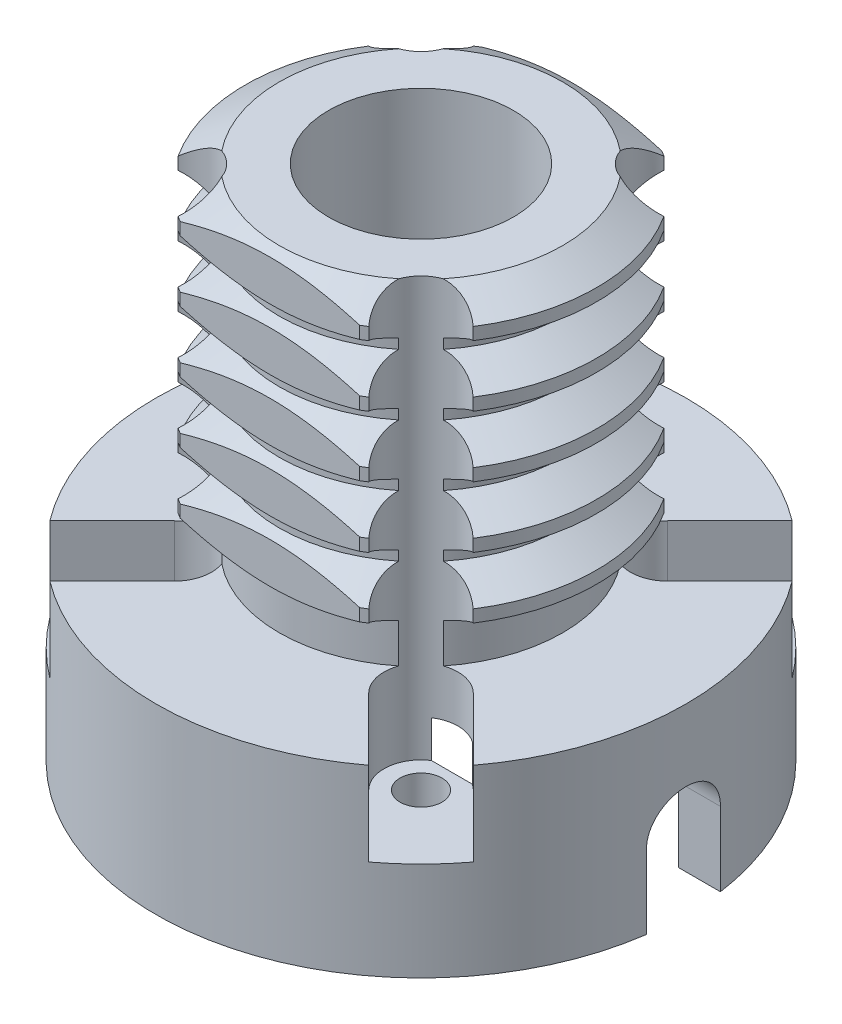
SolidWorks part; units mm, degrees
ref_plane "前视基准面" through (0, 0, 0) normal (0, 0, 1) x (1, 0, 0)
ref_plane "上视基准面" through (0, 0, 0) normal (0, 1, 0) x (1, 0, 0)
ref_plane "右视基准面" through (0, 0, 0) normal (1, 0, 0) x (0, 0, -1)
other "Configuration Table"
sketch "草图1" plane through (0, 0, 0) normal (0, 1, 0) x (1, 0, 0)
  circle A0 centre (0, 0) radius 21.5
  dimension "D1" = 43
extrude "凸台-拉伸1" add sketch "草图1" along normal blind 14.8
sketch "草图2" plane through (0, 0, 0) normal (0, -1, 0) x (1, 0, 0)
  circle A0 centre (0, 0) radius 18.125
  dimension "D1" = 36.25
extrude "切除-拉伸1" cut sketch "草图2" against normal blind 3
sketch "草图3" plane through (0, 14.8, 0) normal (0, 1, 0) x (1, 0, 0)
  circle A0 centre (0, 0) radius 11.5
  dimension "D1" = 23
extrude "凸台-拉伸2" add sketch "草图3" along normal blind 3.2
sketch "草图4" plane through (0, 18, 0) normal (0, 1, 0) x (1, 0, 0)
  circle A0 centre (0, 0) radius 14.25
  dimension "D1" = 28.5
extrude "凸台-拉伸3" add sketch "草图4" along normal blind 24
sketch "草图5" plane through (0, 42, 0) normal (0, 1, 0) x (1, 0, 0)
  circle A0 centre (0, 0) radius 7.5
  dimension "D1" = 15
extrude "切除-拉伸2" cut sketch "草图5" against normal through all
sketch "草图6" plane through (0, 3, 0) normal (0, -1, 0) x (1, 0, 0)
  line L0 (0, 7.5) -> (-5.5, 7.5)
  line L1 (-7.5, 5.5) -> (-7.5, -5.5)
  line L2 (-5.5, -7.5) -> (16.5005, -7.5)
  line L3 (0, 7.5) -> (16.5005, 7.5)
  circle A0 centre (0, 0) radius 7.5 construction
  circle A1 centre (0, 0) radius 18.125 construction
  arc A2 (16.5005, -7.5) -> (16.5005, 7.5) centre (0, 0) ccw
  arc A3 (-7.5, -5.5) -> (-5.5, -7.5) centre (-5.5, -5.5) ccw
  arc A4 (-5.5, 7.5) -> (-7.5, 5.5) centre (-5.5, 5.5) ccw
  dimension "D1" = 2
extrude "切除-拉伸3" cut sketch "草图6" against normal blind 8
ref_plane "基准面1" through (21.5, 0, 0) normal (1, 0, 0) x (0, 0, -1)
sketch "草图7" plane through (21.5, 0, 0) normal (1, 0, 0) x (0, 0, -1)
  line L1 (-3, -6) -> (3, -6)
  line L2 (-3, -6) -> (-3, 6)
  line L3 (-3, 6) -> (3, 6)
  line L4 (3, -6) -> (3, 6)
  line L5 (-3, -6) -> (3, 6) construction
  line L6 (-3, 6) -> (3, -6) construction
  circle A0 centre (0, 6) radius 3
  point P0 (0, 0)
  dimension "D1" = 6
  dimension "D2" = 12
extrude "切除-拉伸4" cut sketch "草图7" against normal blind 8 contours L3 A0 | A0 L2 L1 L4 | L3 A0
sketch "草图8" plane through (0, 0, 0) normal (0, 0, 1) x (1, 0, 0)
  line L0 (0, 42) -> (-11.5, 42)
  line L1 (14.25, 42) -> (-14.25, 42) construction
  line L2 (-11.5, 42) -> (-14.25, 40.42)
  line L3 (-14.25, 42) -> (-14.25, 18) construction
  line L4 (-14.25, 40.42) -> (-14.25, 39.42)
  line L5 (-14.25, 39.42) -> (-11.5, 37.84)
  line L6 (-11.5, 37.84) -> (-11.5, 37.04)
  line L7 (-14.25, 39.92) -> (-11.0784, 39.92) construction
  line L8 (-11.5, 37.04) -> (-14.25, 35.46)
  line L9 (-14.25, 35.46) -> (-14.25, 34.46)
  line L10 (-14.25, 34.46) -> (-11.5, 32.88)
  line L11 (-11.5, 32.88) -> (-11.5, 32.08)
  line L12 (-11.5, 32.08) -> (-14.25, 30.5)
  line L13 (-14.25, 30.5) -> (-14.25, 29.5)
  line L14 (-14.25, 29.5) -> (-11.5, 27.92)
  line L15 (-11.5, 27.92) -> (-11.5, 27.12)
  line L16 (-11.5, 27.12) -> (-14.25, 25.54)
  line L17 (-14.25, 25.54) -> (-14.25, 24.54)
  line L18 (-14.25, 24.54) -> (-11.5, 22.96)
  line L19 (-11.5, 22.96) -> (-11.5, 22.16)
  line L20 (-11.5, 22.16) -> (-14.25, 20.58)
  line L21 (-14.25, 20.58) -> (-14.25, 19.58)
  line L22 (-14.25, 19.58) -> (-11.5, 18)
  line L23 (0, 42) -> (0, 31.5882) construction
  line L24 (-11.5, 42) -> (-16.5, 42)
  line L25 (-16.5, 42) -> (-16.5, 18)
  line L26 (-16.5, 18) -> (-11.5, 18)
  line L28 (-11.5, 18) -> (-11.5, 17.2) [skipped]
  dimension "D1" = 4.16
  dimension "D2" = 1
  dimension "D3" = 0.8
  dimension "D4" = 11.5
  dimension "D5" = 5
  dimension "D6" = 5
revolve "切除-旋转1" cut sketch "草图8" angle 360 about L23
sketch "草图9" plane through (0, 42, 0) normal (0, 1, 0) x (1, 0, 0)
  line L1 (-10, -10) -> (10, -10) construction
  line L2 (-10, -10) -> (-10, 10) construction
  line L3 (-10, 10) -> (10, 10) construction
  line L4 (10, -10) -> (10, 10) construction
  line L5 (-10, -10) -> (10, 10) construction
  line L6 (-10, 10) -> (10, -10) construction
  circle A0 centre (10, 10) radius 3
  circle A1 centre (-10, 10) radius 3
  circle A2 centre (10, -10) radius 3
  circle A3 centre (-10, -10) radius 3
  point P0 (0, 0)
  dimension "D3" = 6
  dimension "D1" = 90
  dimension "D2" = 20
  dimension "D4" = 2
  dimension "D5" = 2
extrude "切除-拉伸5" cut sketch "草图9" against normal offset from surface (34 mm away) 8 up to face at (-0.1151, 0, 0)
sketch "草图10" plane through (0, 14.8, 0) normal (0, 1, 0) x (1, 0, 0)
  line L0 (-12.1213, 12.1213) -> (-15.2028, 15.2028) construction
  line L1 (0, 0) -> (0, 16.22) construction
  line L2 (-11.9729, 7.7302) -> (-17.1754, 12.9327)
  line L3 (-7.8787, 12.1213) -> (-12.9327, 17.1754)
  line L4 (-10, 10) -> (-12.1213, 12.1213) construction
  circle A0 centre (0, 0) radius 21.5 construction
  arc A1 (-12.1213, 12.1213) -> (-12.1213, 7.8787) centre (-10, 10) ccw construction
  circle A2 centre (-10, 10) radius 3 construction
  arc A3 (-12.1213, 7.8787) -> (-7.8787, 12.1213) centre (-10, 10) ccw
  arc A4 (-12.9327, 17.1754) -> (-17.1754, 12.9327) centre (0, 0) ccw
  arc A5 (-7.8787, 12.1213) -> (-12.1213, 12.1213) centre (-10, 10) ccw construction
  arc M7 (-8.9859, 7.1766) -> (-7.1766, 8.9859) centre (-10, 10) cw
  circle M13 centre (0, 0) radius 21.5
  dimension "D1" = 45
extrude "切除-拉伸6" cut sketch "草图10" against normal up to surface (6.8 mm away) contours L3 L2 M7 M13 up to face at (-10, 8, -7)
pattern_circular "阵列(圆周)1" count 4 over 360 about axis through (0, 0, 0) along (0, 1, 0) of "切除-拉伸6"
sketch "草图11" plane through (0, 8, 0) normal (0, 1, 0) x (1, 0, 0)
  arc A0 (-12.1213, 7.8787) -> (-7.8787, 12.1213) centre (-10, 10) ccw construction
  arc A1 (-12.1213, 7.8787) -> (-7.8787, 12.1213) centre (-10, 10) ccw
  circle A2 centre (-10, 10) radius 1.7
  dimension "D1" = 3.4
extrude "切除-拉伸7" cut sketch "草图11" against normal blind 8 contours A2
pattern_circular "阵列(圆周)2" count 4 over 360 about axis through (0, 0, 0) along (0, 1, 0) of "切除-拉伸7"
sketch "草图12" plane through (0, 3, 0) normal (0, -1, 0) x (1, 0, 0)
  circle A0 centre (10, 10) radius 3
extrude "切除-拉伸8" cut sketch "草图12" against normal blind 2.1
pattern_circular "阵列(圆周)3" count 4 over 360 about axis through (0, 0, 0) along (0, 1, 0) of "切除-拉伸8"
sketch "草图13" plane through (0, 14.8, 0) normal (0, 1, 0) x (1, 0, 0)
  line L0 (-15, 12.25) -> (-15, 21.25)
  line L1 (-15, 12.25) -> (15, 12.25)
  line L2 (-15, 12.25) -> (-15, -12.25)
  line L3 (-15, -12.25) -> (15, -12.25)
  line L4 (15, 12.25) -> (15, -12.25)
  line L5 (-15, 12.25) -> (15, -12.25) construction
  line L6 (-15, -12.25) -> (15, 12.25) construction
  line L7 (-15, 21.25) -> (15, 21.25)
  line L8 (15, 21.25) -> (15, 12.25)
  line L9 (-15, -12.25) -> (-15, -21.25)
  line L10 (-15, -21.25) -> (15, -21.25)
  line L11 (15, -21.25) -> (15, -12.25)
  point P0 (0, 0)
  line M6 (7.8787, 12.1213) -> (12.9327, 17.1754)
  arc M7 (12.9327, 17.1754) -> (-12.9327, 17.1754) centre (0, 0) ccw
  line M8 (-12.9327, 17.1754) -> (-7.8787, 12.1213)
  dimension "D1" = 24.5
  dimension "D2" = 30
  dimension "D3" = 9
extrude "切除-拉伸9" cut sketch "草图13" along normal through all contours L10 L11 L3 L9 | L7 L1 M7 M8 M6
